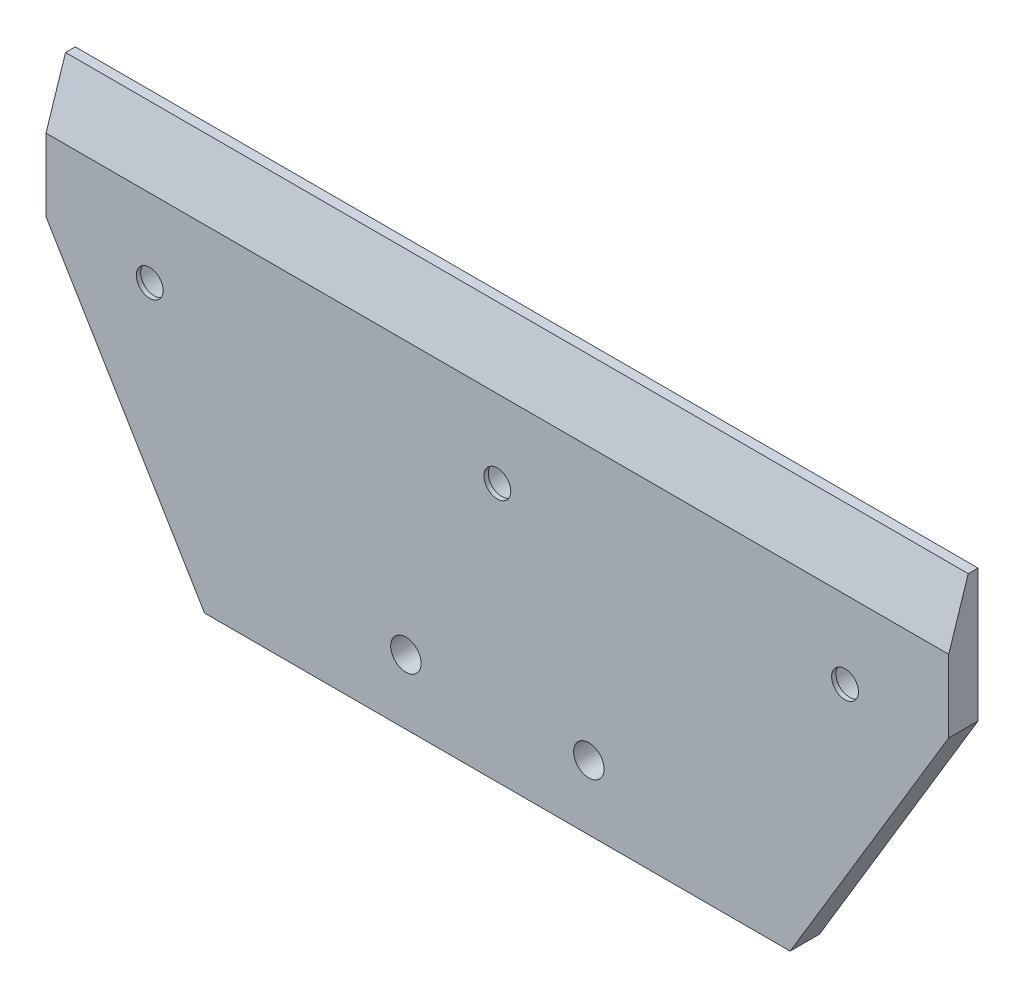
SolidWorks part; units mm, degrees
material "AISI 316 Stainless Steel Sheet (SS)"
ref_plane "Спереди" through (0, 0, 0) normal (0, 0, 1) x (1, 0, 0)
ref_plane "Сверху" through (0, 0, 0) normal (0, 1, 0) x (1, 0, 0)
ref_plane "Справа" through (0, 0, 0) normal (1, 0, 0) x (0, 0, -1)
sketch "Sketch1" plane through (0, 0, 0) normal (0, 0, 1) x (1, 0, 0)
  line L0 (-24, 0) -> (24, 0)
  line L1 (24, 0) -> (37, 21.6356)
  line L2 (37, 21.6356) -> (37, 32.5)
  line L3 (37, 32.5) -> (-37, 32.5)
  line L4 (-37, 32.5) -> (-37, 21.6356)
  line L5 (-37, 21.6356) -> (-24, 0)
  dimension "D1" = 74
  dimension "D2" = 48
  dimension "D3" = 32.5
  dimension "D4" = 121
extrude "Boss-Extrude1" add sketch "Sketch1" along normal mid plane 2.4
sketch "Sketch2" plane through (37, 0, 0) normal (1, 0, 0) x (0, 0, -1)
  line L0 (-1.2, 27.5757) -> (0.4, 32.5)
  line L1 (-1.2, 21.6356) -> (-1.2, 32.5) construction
  line L2 (-1.2, 32.5) -> (1.2, 32.5) construction
  line L3 (-1.2, 27.5757) -> (-1.2, 32.5)
  line L4 (-1.2, 32.5) -> (0.4, 32.5)
  line L8 (1.2, 21.6356) -> (1.2, 32.5) construction
  point P4 (0, 0)
  point P7 (0, 0)
  dimension "D1" = 162
  dimension "D2" = 0.8
extrude "Cut-Extrude1" cut sketch "Sketch2" against normal through all
sketch "Sketch3" plane through (0, 0, 1.2) normal (0, 0, 1) x (1, 0, 0)
  line L0 (-24, 0) -> (24, 0) construction
  point P0 (-7.5, 5.3)
  point P1 (7.5, 5.3)
  dimension "D1" = 5.3
  dimension "D2" = 15
  dimension "D3" = 7.5
hole_wizard "Ø2.5 (2.5) Diameter Hole1" positions "Sketch4" profile "Sketch5" hole size "Ø2.5" standard "ISO"
sketch "Sketch4" plane through (0, 0, 1.2) normal (0, 0, 1) x (1, 0, 0)
  point P0 (-7.5, 5.3)
  point P3 (7.5, 5.3)
sketch "Sketch5" plane through (-7.5, 5.3, 1.2) normal (1, 0, 0) x (0, -1, 0)
  line L0 (0, 0) -> (0, 10.7511)
  line L1 (0, 10.7511) -> (1.25, 10)
  line L2 (1.25, 10) -> (1.25, 0)
  line L5 (1.25, 0) -> (0, 0)
  line L10 (0, 10.7511) -> (-1.25, 10) construction
  line L11 (0, -6.35) -> (0, 107.95) construction
  dimension "Hole Dia." = 2.5
  dimension "Hole Depth" = 10
  dimension "Drill Angle" = 118
sketch "Sketch6" plane through (0, 0, 1.2) normal (0, 0, 1) x (1, 0, 0)
  line L0 (-24, 0) -> (24, 0) construction
  point P0 (0, 21.2)
  point P1 (-28.5, 21.2)
  point P2 (28.5, 21.2)
  dimension "D1" = 57
  dimension "D2" = 28.5
  dimension "D3" = 21.2
sketch "Sketch7" plane through (0, 0, -1.2) normal (0, 0, -1) x (-1, 0, 0)
  line L6 (24, 0) -> (37, 21.6356)
  line L7 (37, 21.6356) -> (37, 32.5)
  line L8 (37, 32.5) -> (-37, 32.5)
  line L9 (-37, 32.5) -> (-37, 21.6356)
  line L10 (-37, 21.6356) -> (-24, 0)
  line L11 (-24, 0) -> (24, 0)
  line L12 (24, 0) -> (37, 21.6356)
  line L13 (37, 21.6356) -> (37, 32.5)
  line L14 (37, 32.5) -> (-37, 32.5)
  line L15 (-37, 32.5) -> (-37, 21.6356)
  line L16 (-37, 21.6356) -> (-24, 0)
  line L17 (-24, 0) -> (24, 0)
  point P2 (-28.5, 21.2)
  point P4 (0, 21.2)
  point P6 (28.5, 21.2)
  dimension "D1" = 0
hole_wizard "HoleWzd1" positions "3DSketch3" profile "Sketch10" legacy end condition up to next
sketch3d "3DSketch3"
  point P0 (28.5, 21.2, -1.2)
  point P3 (0, 21.2, -1.2)
  point P6 (-28.5, 21.2, -1.2)
sketch "Sketch10" plane through (28.5, 21.2, -1.2) normal (1, 0, 0) x (0, 1, 0)
  line L0 (0, 0) -> (0, 2.4)
  line L1 (0, 2.4) -> (1.1, 2.4)
  line L2 (1.1, 2.4) -> (1.1, 2.0408)
  line L3 (1.1, 2.0408) -> (2, 1.5)
  line L4 (2, 1.5) -> (2, 0)
  line L5 (2, 0) -> (0, 0)
  line L6 (0, -6.13) -> (0, 109.2824) construction
  line L7 (-1.1, 2.0408) -> (-2, 1.5) construction
  line L8 (0, 2.4) -> (-1.1, 2.4) construction
  dimension "Diameter" = 2.2
  dimension "Depth" = 2.4
  dimension "C-Drill Diameter" = 4
  dimension "C-Drill Depth" = 1.5
  dimension "C-Drill Angle" = 118
equation "\"D3@Sketch3\"=15/2"
